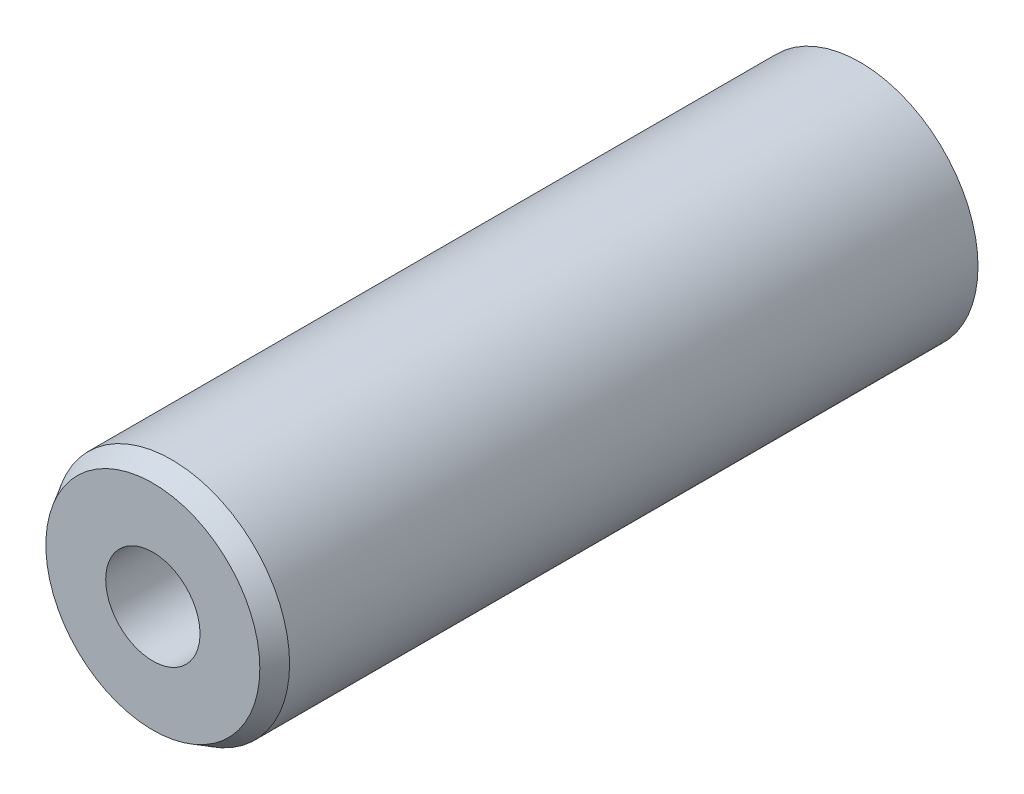
SolidWorks part; units mm, degrees
ref_plane "Front Plane" through (0, 0, 0) normal (0, 0, 1) x (1, 0, 0)
ref_plane "Top Plane" through (0, 0, 0) normal (0, 1, 0) x (1, 0, 0)
ref_plane "Right Plane" through (0, 0, 0) normal (1, 0, 0) x (0, 0, -1)
sketch "Sketch1" plane through (0, 0, 0) normal (0, 0, 1) x (1, 0, 0)
  circle A0 centre (0, 0) radius 2.5
  dimension "D1" = 5
extrude "Boss-Extrude1" add sketch "Sketch1" along normal blind 15
cosmetic thread "Cosmetic Thread2" parameters "D1"=4, "D2"=4.11
sketch "Sketch2" plane through (0, 0, 0) normal (0, 0, -1) x (-1, 0, 0)
  circle A0 centre (0, 0) radius 1
  dimension "D1" = 2
extrude "Cut-Extrude1" cut sketch "Sketch2" against normal through all
hole_wizard "Tap Drill for M4x0.7 Tap1" positions "Sketch4" profile "Sketch3" hole size "M4x0.7" standard "ANSI Metric"
sketch "Sketch4" plane through (0, 0, 0) normal (0, 0, -1) x (-1, 0, 0)
  point P0 (0, 0)
sketch "Sketch3" plane through (0, 0, 0) normal (1, 0, 0) x (0, 1, 0)
  line L0 (0, 0) -> (0, 11.9914)
  line L1 (0, 11.9914) -> (1.65, 11)
  line L2 (1.65, 11) -> (1.65, 0)
  line L5 (1.65, 0) -> (0, 0)
  line L10 (0, 11.9914) -> (-1.65, 11) construction
  line L11 (0, -6.35) -> (0, 107.95) construction
  dimension "Hole Dia." = 3.3
  dimension "Hole Depth" = 11
  dimension "Drill Angle" = 118
cosmetic thread "Cosmetic Thread3" parameters "D1"=10, "D2"=4
chamfer "Chamfer1" distance 0.4 angle 30 1 edges at (2.5, 0, 15)
chamfer "Chamfer2" distance 0.5 angle 60 1 edges at (-1.65, 0, 0)
